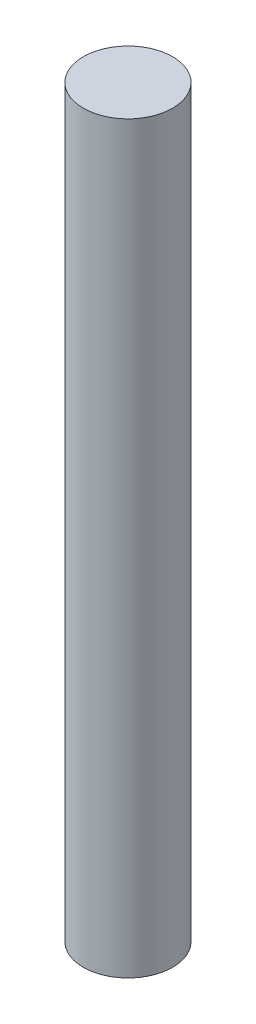
SolidWorks part; units mm, degrees
material "镀铬不锈钢"
ref_plane "前视基准面" through (0, 0, 0) normal (0, 0, 1) x (1, 0, 0)
ref_plane "上视基准面" through (0, 0, 0) normal (0, 1, 0) x (1, 0, 0)
ref_plane "右视基准面" through (0, 0, 0) normal (1, 0, 0) x (0, 0, -1)
sketch "草图1" plane through (0, 0, 0) normal (0, 1, 0) x (1, 0, 0)
  circle A0 centre (0, 0) radius 1.5
  dimension "D1" = 3
extrude "凸台-拉伸1" add sketch "草图1" along normal blind 25
